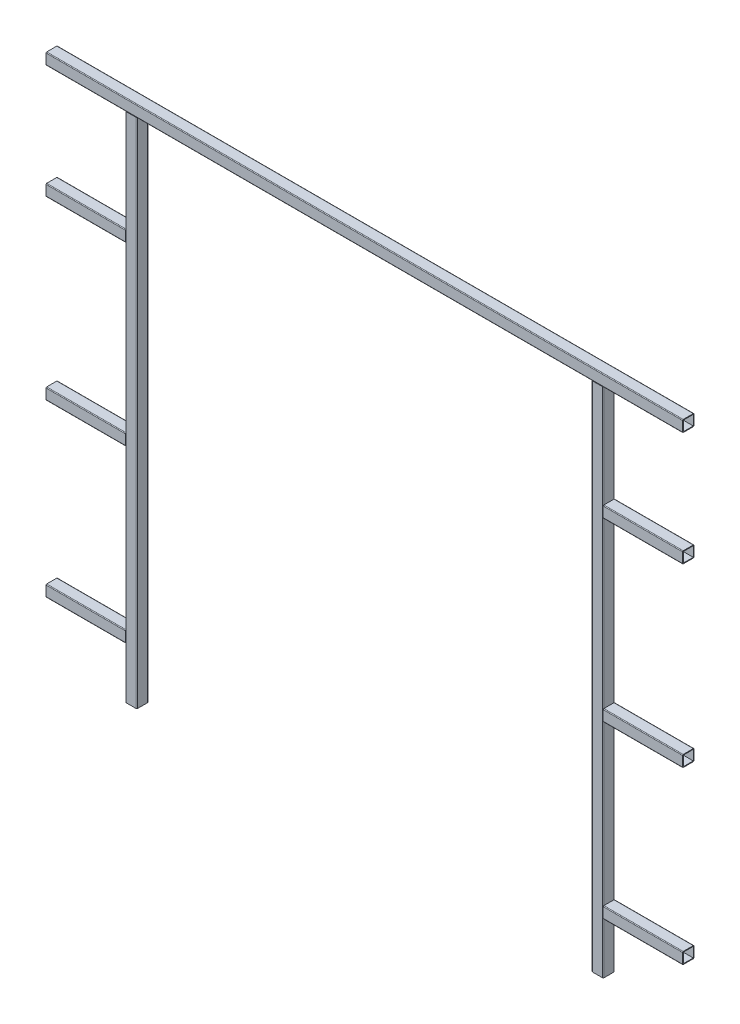
SolidWorks part; units mm, degrees
material "Простая углеродистая сталь"
ref_plane "Спереди" through (0, 0, 0) normal (0, 0, 1) x (1, 0, 0)
ref_plane "Сверху" through (0, 0, 0) normal (0, 1, 0) x (1, 0, 0)
ref_plane "Справа" through (0, 0, 0) normal (1, 0, 0) x (0, 0, -1)
sketch "Эскиз1" plane through (0, 0, 0) normal (0, 0, 1) x (1, 0, 0)
  line L0 (0, 0) -> (5595, 0)
  line L1 (747.5, 0) -> (747.5, -4550)
  line L2 (2797.5, 0) -> (2797.5, -1000) construction
  line L3 (4847.5, 0) -> (4847.5, -4550)
  line L4 (747.5, -4050) -> (0, -4050)
  line L5 (747.5, -1000) -> (0, -1000)
  line L6 (4847.5, -1000) -> (5595, -1000)
  line L7 (4847.5, -4050) -> (5595, -4050)
  line L8 (747.5, -2550) -> (0, -2550)
  line L9 (4847.5, -2550) -> (5595, -2550)
  dimension "D1" = 5595
  dimension "D2" = 4550
  dimension "D3" = 4100
  dimension "D4" = 500
  dimension "D5" = 1000
  dimension "D6" = 1500
other "Квадратная труба гост 8639-82 100 X 100 X 6.0(1)"
ref_plane "Плоскость1" through (0, 0, 0) normal (1, 0, 0) x (0, 1, 0)
sketch "Sketch1" plane through (0, 0, 0) normal (1, 0, 0) x (0, 1, 0)
  line L0 (-43.999, -44) -> (43.999, -44)
  line L1 (-44, -43.999) -> (-44, 43.999)
  line L2 (43.999, 44) -> (-43.999, 44)
  line L3 (44, 43.999) -> (44, -43.999)
  line L4 (-43.999, -50) -> (43.999, -50)
  line L5 (-50, -43.999) -> (-50, 43.999)
  line L6 (43.999, 50) -> (-43.999, 50)
  line L7 (50, 43.999) -> (50, -43.999)
  arc A0 (50, 43.999) -> (43.999, 50) centre (43.999, 43.999) ccw
  arc A1 (43.999, -50) -> (50, -43.999) centre (43.999, -43.999) ccw
  arc A2 (-50, -43.999) -> (-43.999, -50) centre (-43.999, -43.999) ccw
  arc A3 (-43.999, 50) -> (-50, 43.999) centre (-43.999, 43.999) ccw
  arc A4 (-43.999, 44) -> (-44, 43.999) centre (-43.999, 43.999) ccw
  arc A5 (44, 43.999) -> (43.999, 44) centre (43.999, 43.999) ccw
  arc A6 (43.999, -44) -> (44, -43.999) centre (43.999, -43.999) ccw
  arc A7 (-44, -43.999) -> (-43.999, -44) centre (-43.999, -43.999) ccw
  point P0 (-50, 0)
  point P1 (50, 0)
  point P2 (0, 50)
  point P3 (0, -50)
  point P4 (0, 0)
  point P5 (-50, -50)
  point P6 (50, -50)
  point P7 (50, 50)
  point P8 (-50, 50)
  point P33 (0, 0)
  dimension "D1" = 6.001
  dimension "Thickness" = 6
  dimension "V_leg" = 100
equation "\"D1@Sketch1\" = \"Thickness@Sketch1\"+0.001"
